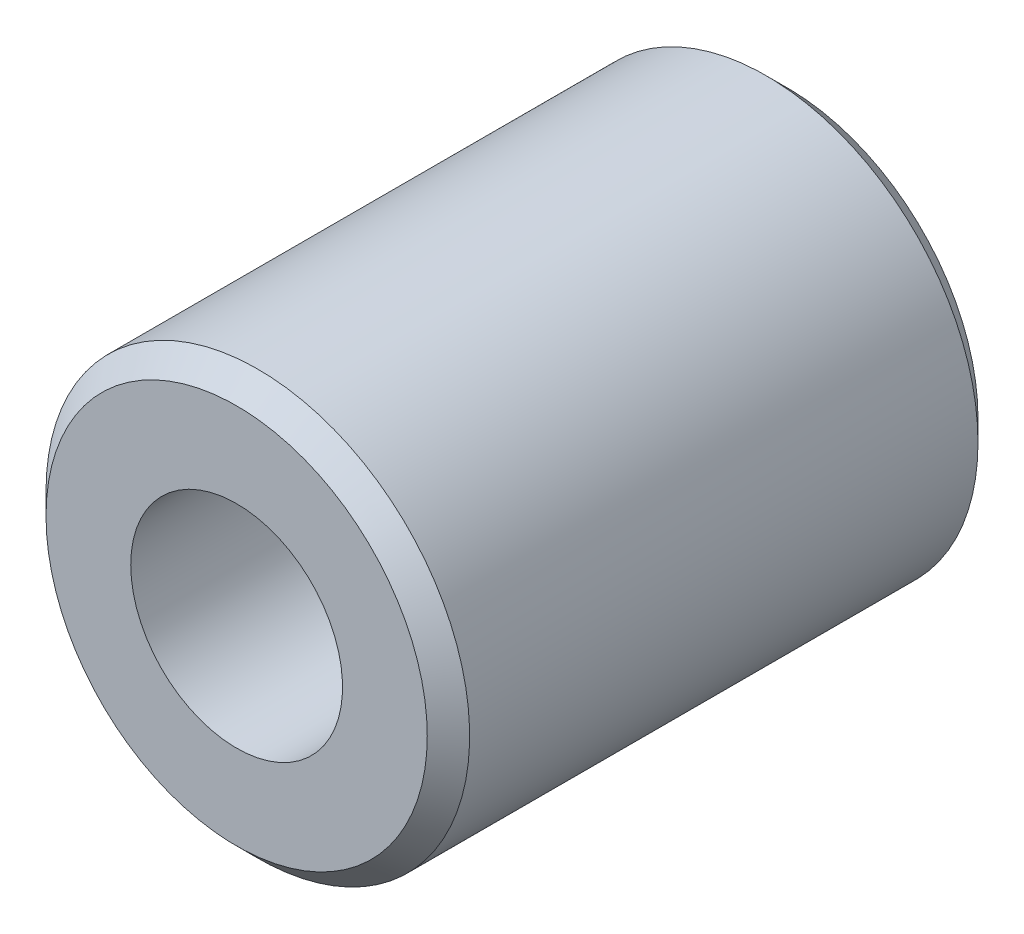
SolidWorks part; units mm, degrees
ref_plane "Front" through (0, 0, 0) normal (0, 0, 1) x (1, 0, 0)
ref_plane "Top" through (0, 0, 0) normal (0, 1, 0) x (1, 0, 0)
ref_plane "Right" through (0, 0, 0) normal (1, 0, 0) x (0, 0, -1)
sketch "Sketch1" plane through (0, 0, 0) normal (0, 0, 1) x (1, 0, 0)
  circle A0 centre (0, 0) radius 2.5
  circle A1 centre (0, 0) radius 5
  dimension "D1" = 5
  dimension "D2" = 2.5
extrude "Boss-Extrude1" add sketch "Sketch1" along normal blind 13
chamfer "Chamfer1" distance 0.5 angle 45 2 edges at (5, 0, 0) (5, 0, 13)
